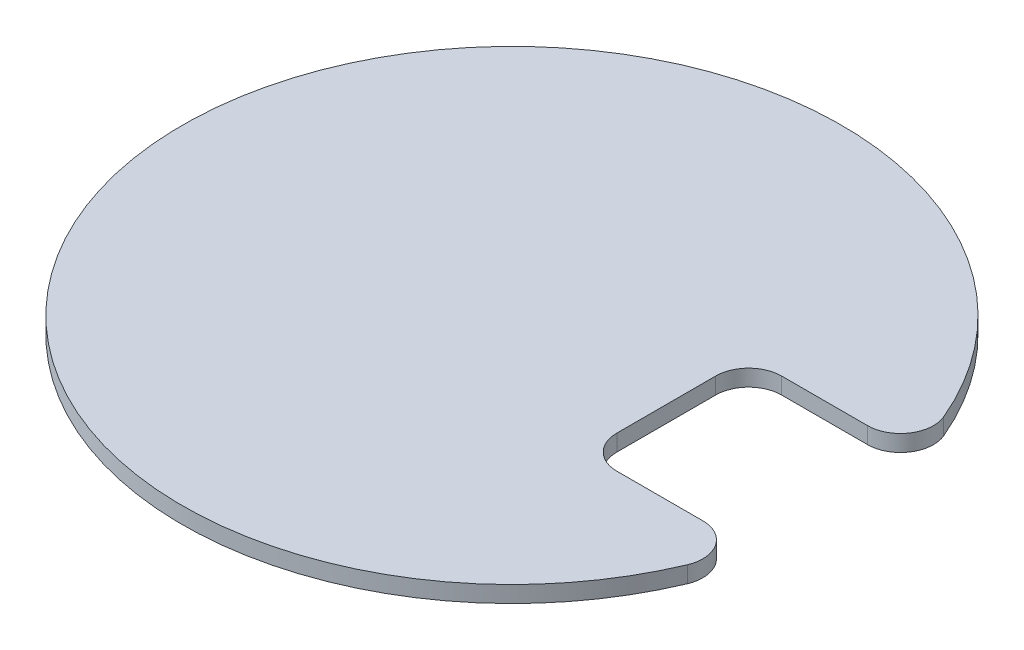
SolidWorks part; units mm, degrees
ref_plane "Front Plane" through (0, 0, 0) normal (0, 0, 1) x (1, 0, 0)
ref_plane "Top Plane" through (0, 0, 0) normal (0, 1, 0) x (1, 0, 0)
ref_plane "Right Plane" through (0, 0, 0) normal (1, 0, 0) x (0, 0, -1)
sketch "Sketch1" plane through (0, 0, 0) normal (0, 1, 0) x (1, 0, 0)
  line L1 (16.5831, 5) -> (11.3649, 5)
  line L2 (9.3649, 3) -> (9.3649, -3)
  line L3 (11.3649, -5) -> (16.5831, -5)
  arc A0 (18.4257, 7.7778) -> (18.4257, -7.7778) centre (0, 0) ccw
  arc A1 (11.3649, 5) -> (9.3649, 3) centre (11.3649, 3) ccw
  arc A2 (9.3649, -3) -> (11.3649, -5) centre (11.3649, -3) ccw
  arc A3 (18.4257, -7.7778) -> (16.5831, -5) centre (16.5831, -7) ccw
  arc A4 (18.4257, 7.7778) -> (16.5831, 5) centre (16.5831, 7) cw
  point P8 (9.3649, 5)
  point P13 (19.3649, -5)
  point P16 (19.3649, 5)
  dimension "D1" = 40
  dimension "D4" = 2
  dimension "D2" = 10
  dimension "D3" = 10
extrude "Boss-Extrude1" add sketch "Sketch1" along normal blind 1
